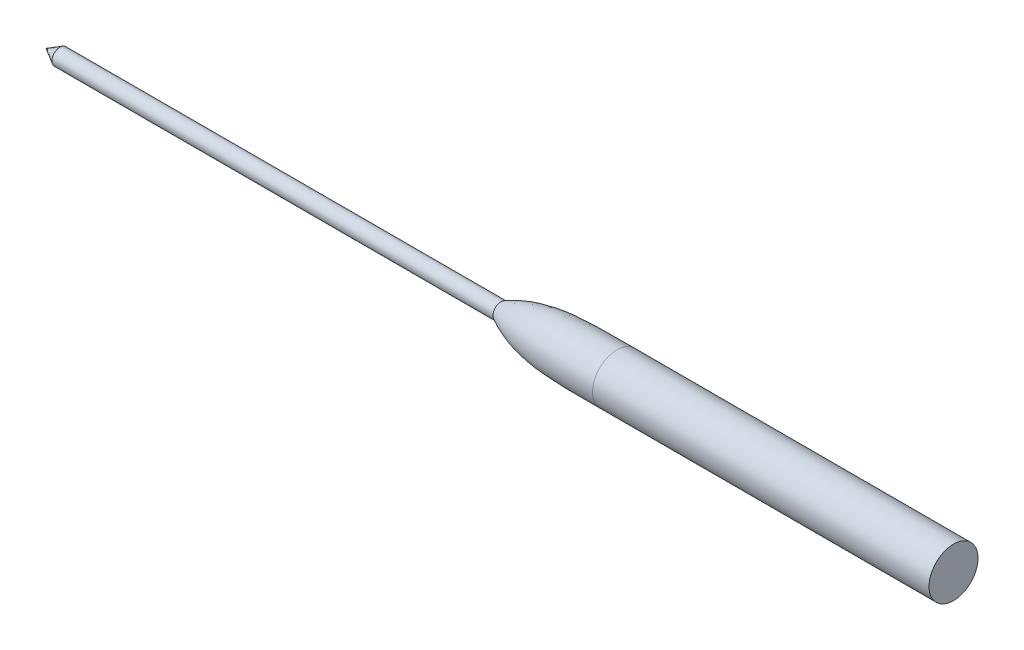
SolidWorks part; units mm, degrees
ref_plane "Ebene vorne" through (0, 0, 0) normal (0, 0, 1) x (1, 0, 0)
ref_plane "Ebene oben" through (0, 0, 0) normal (0, 1, 0) x (1, 0, 0)
ref_plane "Ebene rechts" through (0, 0, 0) normal (1, 0, 0) x (0, 0, -1)
sketch "Skizze1" plane through (0, 0, 0) normal (0, 1, 0) x (1, 0, 0)
  line L0 (-693, -12.75) -> (-703.8253, -19)
  line L1 (-703.8253, -19) -> (0, -19)
  line L2 (0, 0) -> (-261, 0)
  line L3 (-351, -12.75) -> (-693, -12.75)
  line L4 (0, -19) -> (0, 0)
  spline S0 degree 3 poles (-261, 0) (-291.1127, 0) (-323.6389, 1.8763) (-351, -12.75) knots 0 0 0 0 1 1 1 1
  dimension "D5" = 342
  dimension "D1" = 19
  dimension "D2" = 261
  dimension "D3" = 90
  dimension "D4" = 6.25
  dimension "D6" = 30
revolve "Rotation1" add sketch "Skizze1" angle 360 about L1
